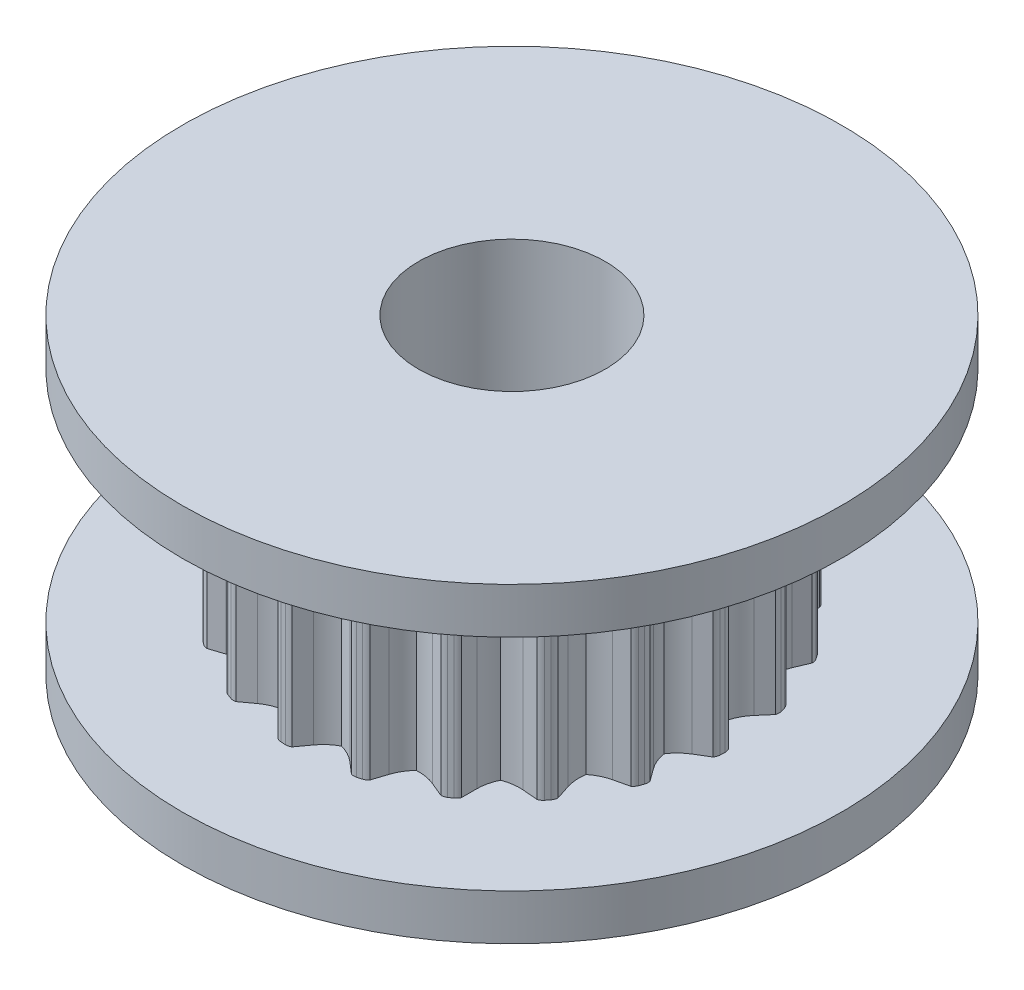
SolidWorks part; units mm, degrees
ref_plane "前视基准面" through (0, 0, 0) normal (0, 0, 1) x (1, 0, 0)
ref_plane "上视基准面" through (0, 0, 0) normal (0, 1, 0) x (1, 0, 0)
ref_plane "右视基准面" through (0, 0, 0) normal (1, 0, 0) x (0, 0, -1)
other "Configuration Table"
sketch "草图1" plane through (0, 0, 0) normal (0, 1, 0) x (1, 0, 0)
  line L2 (-3.3768, 4.9596) -> (-3.2674, 5.0323)
  line L3 (-3.4667, 4.8471) -> (-3.4667, 4.4267)
  line L4 (-3.1289, 5.0717) -> (-2.7413, 4.9091)
  line L5 (-1.6789, 5.7603) -> (-1.5524, 5.7957)
  line L6 (-1.7992, 5.6811) -> (-1.9291, 5.2813)
  line L7 (-1.4085, 5.7904) -> (-1.0901, 5.5159)
  line L8 (0.1833, 5.9972) -> (0.3145, 5.9918)
  line L9 (0.0445, 5.9591) -> (-0.2026, 5.619)
  line L10 (0.4497, 5.9422) -> (0.6678, 5.5828)
  line L11 (2.0276, 5.647) -> (2.1507, 5.6013)
  line L12 (1.8837, 5.6537) -> (1.5436, 5.4066)
  line L13 (2.264, 5.5124) -> (2.3603, 5.1032)
  line L14 (3.6734, 4.7441) -> (3.7763, 4.6626)
  line L15 (3.5386, 4.7949) -> (3.1388, 4.665)
  line L16 (3.8566, 4.543) -> (3.8218, 4.1241)
  line L17 (4.9596, 3.3768) -> (5.0323, 3.2674)
  line L18 (4.8471, 3.4667) -> (4.4267, 3.4667)
  line L19 (5.0717, 3.1289) -> (4.9091, 2.7413)
  line L20 (5.7603, 1.6789) -> (5.7957, 1.5524)
  line L21 (5.6811, 1.7992) -> (5.2813, 1.9291)
  line L22 (5.7904, 1.4085) -> (5.5159, 1.0901)
  line L23 (5.9972, -0.1833) -> (5.9918, -0.3145)
  line L24 (5.9591, -0.0445) -> (5.619, 0.2026)
  line L25 (5.9422, -0.4497) -> (5.5828, -0.6678)
  line L26 (5.647, -2.0276) -> (5.6013, -2.1507)
  line L27 (5.6537, -1.8837) -> (5.4066, -1.5436)
  line L28 (5.5124, -2.264) -> (5.1032, -2.3603)
  line L29 (4.7441, -3.6734) -> (4.6626, -3.7763)
  line L30 (4.7949, -3.5386) -> (4.665, -3.1388)
  line L31 (4.543, -3.8566) -> (4.1241, -3.8218)
  line L32 (3.3768, -4.9596) -> (3.2674, -5.0323)
  line L33 (3.4667, -4.8471) -> (3.4667, -4.4267)
  line L34 (3.1289, -5.0717) -> (2.7413, -4.9091)
  line L35 (1.6789, -5.7603) -> (1.5524, -5.7957)
  line L36 (1.7992, -5.6811) -> (1.9291, -5.2813)
  line L37 (1.4085, -5.7904) -> (1.0901, -5.5159)
  line L38 (-0.1833, -5.9972) -> (-0.3145, -5.9918)
  line L39 (-0.0445, -5.9591) -> (0.2026, -5.619)
  line L40 (-0.4497, -5.9422) -> (-0.6678, -5.5828)
  line L41 (-2.0276, -5.647) -> (-2.1507, -5.6013)
  line L42 (-1.8837, -5.6537) -> (-1.5436, -5.4066)
  line L43 (-2.264, -5.5124) -> (-2.3603, -5.1032)
  line L44 (-3.6734, -4.7441) -> (-3.7763, -4.6626)
  line L45 (-3.5386, -4.7949) -> (-3.1388, -4.665)
  line L46 (-3.8566, -4.543) -> (-3.8218, -4.1241)
  line L47 (-4.9596, -3.3768) -> (-5.0323, -3.2674)
  line L48 (-4.8471, -3.4667) -> (-4.4267, -3.4667)
  line L49 (-5.0717, -3.1289) -> (-4.9091, -2.7413)
  line L50 (-5.7603, -1.6789) -> (-5.7957, -1.5524)
  line L51 (-5.6811, -1.7992) -> (-5.2813, -1.9291)
  line L52 (-5.7904, -1.4085) -> (-5.5159, -1.0901)
  line L53 (-5.9972, 0.1833) -> (-5.9918, 0.3145)
  line L54 (-5.9591, 0.0445) -> (-5.619, -0.2026)
  line L55 (-5.9422, 0.4497) -> (-5.5828, 0.6678)
  line L56 (-5.647, 2.0276) -> (-5.6013, 2.1507)
  line L57 (-5.6537, 1.8837) -> (-5.4066, 1.5436)
  line L58 (-5.5124, 2.264) -> (-5.1032, 2.3603)
  line L59 (-4.7441, 3.6734) -> (-4.6626, 3.7763)
  line L60 (-4.7949, 3.5386) -> (-4.665, 3.1388)
  line L61 (-4.543, 3.8566) -> (-4.1241, 3.8218)
  arc A1 (-3.4667, 4.4267) -> (-3.5892, 3.9002) centre (-4.6588, 4.4267) cw
  arc A2 (-3.3768, 4.9596) -> (-3.4667, 4.8471) centre (-3.2292, 4.7494) ccw
  arc A3 (-2.7413, 4.9091) -> (-2.2083, 4.8185) centre (-2.2801, 6.0085) ccw
  arc A4 (-3.2674, 5.0323) -> (-3.1289, 5.0717) centre (-3.1307, 4.8149) cw
  arc A5 (-1.9291, 5.2813) -> (-2.2083, 4.8185) centre (-3.0629, 5.6497) cw
  arc A6 (-1.6789, 5.7603) -> (-1.7992, 5.6811) centre (-1.6035, 5.5148) ccw
  arc A7 (-1.5524, 5.7957) -> (-1.4085, 5.7904) centre (-1.4896, 5.5467) cw
  arc A8 (-1.0901, 5.5159) -> (-0.6113, 5.2651) centre (-0.3118, 6.419) ccw
  arc A9 (-0.2026, 5.619) -> (-0.6113, 5.2651) centre (-1.1671, 6.3197) cw
  arc A10 (0.1833, 5.9972) -> (0.0445, 5.9591) centre (0.1792, 5.7404) ccw
  arc A11 (0.3145, 5.9918) -> (0.4497, 5.9422) centre (0.2974, 5.7355) cw
  arc A12 (0.6678, 5.5828) -> (1.0457, 5.1963) centre (1.687, 6.2012) ccw
  arc A13 (1.5436, 5.4066) -> (1.0457, 5.1963) centre (0.8429, 6.371) cw
  arc A14 (2.0276, 5.647) -> (1.8837, 5.6537) centre (1.9443, 5.4041) ccw
  arc A15 (2.1507, 5.6013) -> (2.264, 5.5124) centre (2.0552, 5.3629) cw
  arc A16 (2.3603, 5.1032) -> (2.6002, 4.6188) centre (3.5207, 5.3764) ccw
  arc A17 (3.1388, 4.665) -> (2.6002, 4.6188) centre (2.7704, 5.7987) cw
  arc A18 (3.6734, 4.7441) -> (3.5386, 4.7949) centre (3.5191, 4.5388) ccw
  arc A19 (3.7763, 4.6626) -> (3.8566, 4.543) centre (3.6118, 4.4653) cw
  arc A20 (3.8218, 4.1241) -> (3.9002, 3.5892) centre (5.0098, 4.0253) ccw
  arc A21 (4.4267, 3.4667) -> (3.9002, 3.5892) centre (4.4267, 4.6588) cw
  arc A22 (4.9596, 3.3768) -> (4.8471, 3.4667) centre (4.7494, 3.2292) ccw
  arc A23 (5.0323, 3.2674) -> (5.0717, 3.1289) centre (4.8149, 3.1307) cw
  arc A24 (4.9091, 2.7413) -> (4.8185, 2.2083) centre (6.0085, 2.2801) ccw
  arc A25 (5.2813, 1.9291) -> (4.8185, 2.2083) centre (5.6497, 3.0629) cw
  arc A26 (5.7603, 1.6789) -> (5.6811, 1.7992) centre (5.5148, 1.6035) ccw
  arc A27 (5.7957, 1.5524) -> (5.7904, 1.4085) centre (5.5467, 1.4896) cw
  arc A28 (5.5159, 1.0901) -> (5.2651, 0.6113) centre (6.419, 0.3118) ccw
  arc A29 (5.619, 0.2026) -> (5.2651, 0.6113) centre (6.3197, 1.1671) cw
  arc A30 (5.9972, -0.1833) -> (5.9591, -0.0445) centre (5.7404, -0.1792) ccw
  arc A31 (5.9918, -0.3145) -> (5.9422, -0.4497) centre (5.7355, -0.2974) cw
  arc A32 (5.5828, -0.6678) -> (5.1963, -1.0457) centre (6.2012, -1.687) ccw
  arc A33 (5.4066, -1.5436) -> (5.1963, -1.0457) centre (6.371, -0.8429) cw
  arc A34 (5.647, -2.0276) -> (5.6537, -1.8837) centre (5.4041, -1.9443) ccw
  arc A35 (5.6013, -2.1507) -> (5.5124, -2.264) centre (5.3629, -2.0552) cw
  arc A36 (5.1032, -2.3603) -> (4.6188, -2.6002) centre (5.3764, -3.5207) ccw
  arc A37 (4.665, -3.1388) -> (4.6188, -2.6002) centre (5.7987, -2.7704) cw
  arc A38 (4.7441, -3.6734) -> (4.7949, -3.5386) centre (4.5388, -3.5191) ccw
  arc A39 (4.6626, -3.7763) -> (4.543, -3.8566) centre (4.4653, -3.6118) cw
  arc A40 (4.1241, -3.8218) -> (3.5892, -3.9002) centre (4.0253, -5.0098) ccw
  arc A41 (3.4667, -4.4267) -> (3.5892, -3.9002) centre (4.6588, -4.4267) cw
  arc A42 (3.3768, -4.9596) -> (3.4667, -4.8471) centre (3.2292, -4.7494) ccw
  arc A43 (3.2674, -5.0323) -> (3.1289, -5.0717) centre (3.1307, -4.8149) cw
  arc A44 (2.7413, -4.9091) -> (2.2083, -4.8185) centre (2.2801, -6.0085) ccw
  arc A45 (1.9291, -5.2813) -> (2.2083, -4.8185) centre (3.0629, -5.6497) cw
  arc A46 (1.6789, -5.7603) -> (1.7992, -5.6811) centre (1.6035, -5.5148) ccw
  arc A47 (1.5524, -5.7957) -> (1.4085, -5.7904) centre (1.4896, -5.5467) cw
  arc A48 (1.0901, -5.5159) -> (0.6113, -5.2651) centre (0.3118, -6.419) ccw
  arc A49 (0.2026, -5.619) -> (0.6113, -5.2651) centre (1.1671, -6.3197) cw
  arc A50 (-0.1833, -5.9972) -> (-0.0445, -5.9591) centre (-0.1792, -5.7404) ccw
  arc A51 (-0.3145, -5.9918) -> (-0.4497, -5.9422) centre (-0.2974, -5.7355) cw
  arc A52 (-0.6678, -5.5828) -> (-1.0457, -5.1963) centre (-1.687, -6.2012) ccw
  arc A53 (-1.5436, -5.4066) -> (-1.0457, -5.1963) centre (-0.8429, -6.371) cw
  arc A54 (-2.0276, -5.647) -> (-1.8837, -5.6537) centre (-1.9443, -5.4041) ccw
  arc A55 (-2.1507, -5.6013) -> (-2.264, -5.5124) centre (-2.0552, -5.3629) cw
  arc A56 (-2.3603, -5.1032) -> (-2.6002, -4.6188) centre (-3.5207, -5.3764) ccw
  arc A57 (-3.1388, -4.665) -> (-2.6002, -4.6188) centre (-2.7704, -5.7987) cw
  arc A58 (-3.6734, -4.7441) -> (-3.5386, -4.7949) centre (-3.5191, -4.5388) ccw
  arc A59 (-3.7763, -4.6626) -> (-3.8566, -4.543) centre (-3.6118, -4.4653) cw
  arc A60 (-3.8218, -4.1241) -> (-3.9002, -3.5892) centre (-5.0098, -4.0253) ccw
  arc A61 (-4.4267, -3.4667) -> (-3.9002, -3.5892) centre (-4.4267, -4.6588) cw
  arc A62 (-4.9596, -3.3768) -> (-4.8471, -3.4667) centre (-4.7494, -3.2292) ccw
  arc A63 (-5.0323, -3.2674) -> (-5.0717, -3.1289) centre (-4.8149, -3.1307) cw
  arc A64 (-4.9091, -2.7413) -> (-4.8185, -2.2083) centre (-6.0085, -2.2801) ccw
  arc A65 (-5.2813, -1.9291) -> (-4.8185, -2.2083) centre (-5.6497, -3.0629) cw
  arc A66 (-5.7603, -1.6789) -> (-5.6811, -1.7992) centre (-5.5148, -1.6035) ccw
  arc A67 (-5.7957, -1.5524) -> (-5.7904, -1.4085) centre (-5.5467, -1.4896) cw
  arc A68 (-5.5159, -1.0901) -> (-5.2651, -0.6113) centre (-6.419, -0.3118) ccw
  arc A69 (-5.619, -0.2026) -> (-5.2651, -0.6113) centre (-6.3197, -1.1671) cw
  arc A70 (-5.9972, 0.1833) -> (-5.9591, 0.0445) centre (-5.7404, 0.1792) ccw
  arc A71 (-5.9918, 0.3145) -> (-5.9422, 0.4497) centre (-5.7355, 0.2974) cw
  arc A72 (-5.5828, 0.6678) -> (-5.1963, 1.0457) centre (-6.2012, 1.687) ccw
  arc A73 (-5.4066, 1.5436) -> (-5.1963, 1.0457) centre (-6.371, 0.8429) cw
  arc A74 (-5.647, 2.0276) -> (-5.6537, 1.8837) centre (-5.4041, 1.9443) ccw
  arc A75 (-5.6013, 2.1507) -> (-5.5124, 2.264) centre (-5.3629, 2.0552) cw
  arc A76 (-5.1032, 2.3603) -> (-4.6188, 2.6002) centre (-5.3764, 3.5207) ccw
  arc A77 (-4.665, 3.1388) -> (-4.6188, 2.6002) centre (-5.7987, 2.7704) cw
  arc A78 (-4.7441, 3.6734) -> (-4.7949, 3.5386) centre (-4.5388, 3.5191) ccw
  arc A79 (-4.6626, 3.7763) -> (-4.543, 3.8566) centre (-4.4653, 3.6118) cw
  arc A80 (-4.1241, 3.8218) -> (-3.5892, 3.9002) centre (-4.0253, 5.0098) ccw
  point P247 (0, 0)
  dimension "D1" = 20
extrude "凸台-拉伸1" add sketch "草图1" along normal mid plane 6
sketch "草图3" plane through (0, 3, 0) normal (0, 1, 0) x (1, 0, 0)
  circle A0 centre (0, 0) radius 9
  dimension "D1" = 18
extrude "凸台-拉伸2" add sketch "草图3" along normal blind 1.25
mirror "镜向1" about plane through (0, 0, 0) normal (0, 1, 0) of "凸台-拉伸2"
sketch "草图4" plane through (0, 4.25, 0) normal (0, 1, 0) x (1, 0, 0)
  circle A0 centre (0, 0) radius 2.55
  dimension "D1" = 5.1
extrude "切除-拉伸1" cut sketch "草图4" against normal through all
